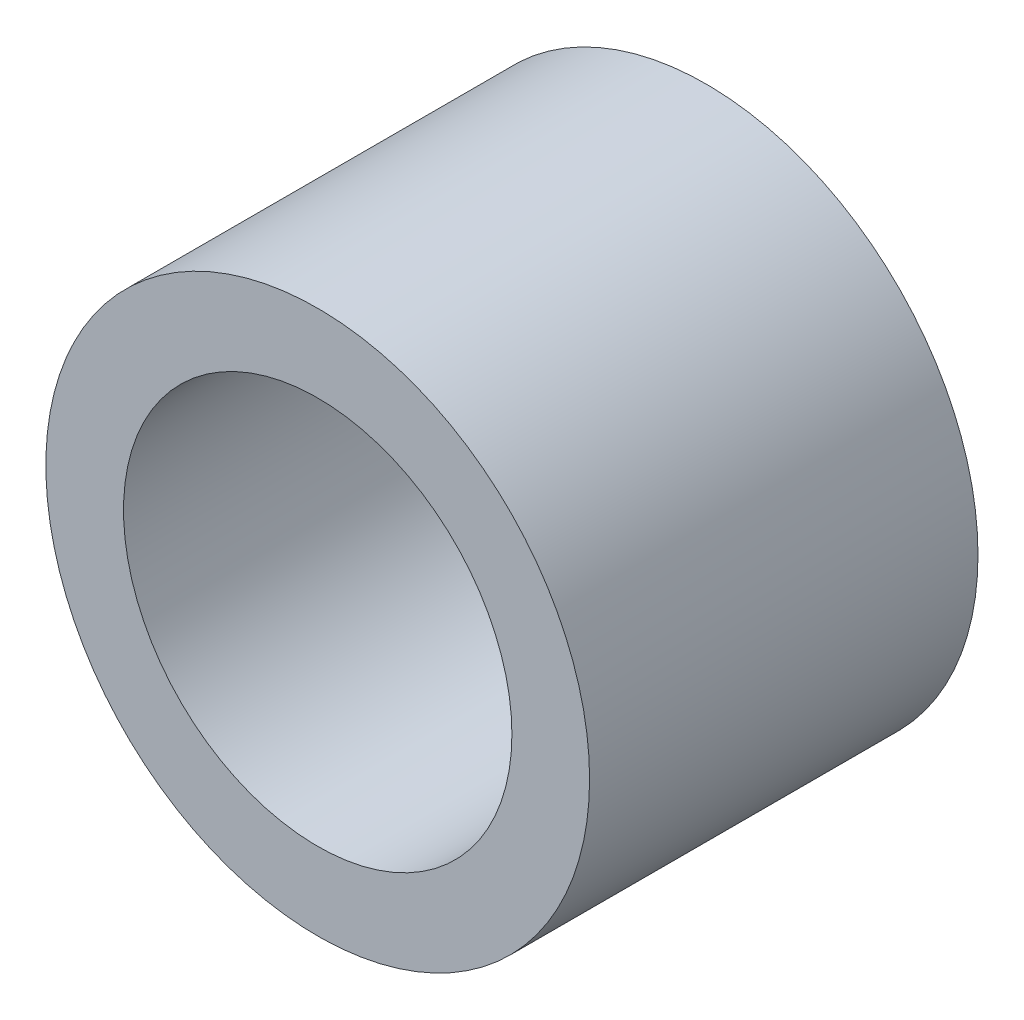
SolidWorks part; units mm, degrees
material "合金钢"
ref_plane "前视基准面" through (0, 0, 0) normal (0, 0, 1) x (1, 0, 0)
ref_plane "上视基准面" through (0, 0, 0) normal (0, 1, 0) x (1, 0, 0)
ref_plane "右视基准面" through (0, 0, 0) normal (1, 0, 0) x (0, 0, -1)
other "Configuration Table"
sketch "草图1" plane through (0, 0, 0) normal (0, 0, 1) x (1, 0, 0)
  line L0 (-2.8496, 0) -> (2.3048, 0) construction
  line L1 (0, 1.6553) -> (0, -2.221) construction
  circle A0 centre (0, 0) radius 2.5
  circle A1 centre (0, 0) radius 3.5
  dimension "D1" = 5
  dimension "D2" = 7
extrude "凸台-拉伸1" add sketch "草图1" along normal mid plane 5
